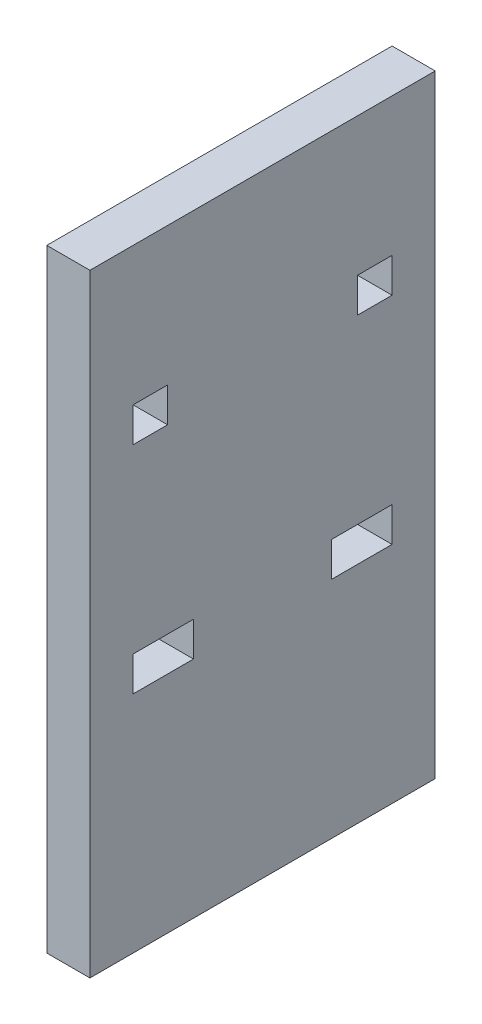
SolidWorks part; units mm, degrees
material "Mahogany"
ref_plane "Front Plane" through (0, 0, 0) normal (0, 0, 1) x (1, 0, 0)
ref_plane "Top Plane" through (0, 0, 0) normal (0, 1, 0) x (1, 0, 0)
ref_plane "Right Plane" through (0, 0, 0) normal (1, 0, 0) x (0, 0, -1)
sketch "Sketch1" plane through (0, 0, 0) normal (0, 1, 0) x (1, 0, 0)
  line L1 (-2.5, 20) -> (2.5, 20)
  line L2 (-2.5, 20) -> (-2.5, -20)
  line L3 (-2.5, -20) -> (2.5, -20)
  line L4 (2.5, 20) -> (2.5, -20)
  line L5 (-2.5, 20) -> (2.5, -20) construction
  line L6 (-2.5, -20) -> (2.5, 20) construction
  point P0 (0, 0)
  dimension "D1" = 40
  dimension "D2" = 5
extrude "Boss-Extrude1" add sketch "Sketch1" along normal blind 71
sketch "Sketch2" plane through (2.5, 0, 0) normal (1, 0, 0) x (0, 0, -1)
  line L0 (-20, 0) -> (20, 0) construction
  line L1 (-15, 30) -> (-8, 30)
  line L2 (-15, 30) -> (-15, 26)
  line L3 (-15, 26) -> (-8, 26)
  line L4 (-8, 30) -> (-8, 26)
  line L5 (-15, 30) -> (-8, 26) construction
  line L6 (-15, 26) -> (-8, 30) construction
  line L7 (-20, 71) -> (-20, 0) construction
  line L8 (0, 0) -> (0, 71) construction
  line L9 (-20, 71) -> (20, 71) construction
  line L10 (15, 26) -> (8, 30) construction
  line L11 (15, 30) -> (8, 26) construction
  line L12 (8, 30) -> (8, 26)
  line L13 (15, 26) -> (8, 26)
  line L14 (15, 30) -> (15, 26)
  line L15 (15, 30) -> (8, 30)
  line L16 (-15, 55) -> (-11, 55)
  line L17 (-15, 55) -> (-15, 51)
  line L18 (-15, 51) -> (-11, 51)
  line L19 (-11, 55) -> (-11, 51)
  line L20 (-15, 55) -> (-11, 51) construction
  line L21 (-15, 51) -> (-11, 55) construction
  line L22 (15, 51) -> (11, 55) construction
  line L23 (15, 55) -> (11, 51) construction
  line L24 (11, 55) -> (11, 51)
  line L25 (15, 51) -> (11, 51)
  line L26 (15, 55) -> (15, 51)
  line L27 (15, 55) -> (11, 55)
  point P0 (-11.5, 28)
  point P18 (11.5, 28)
  point P19 (-13, 53)
  point P29 (13, 53)
  dimension "D1" = 26
  dimension "D2" = 5
  dimension "D3" = 7
  dimension "D4" = 4
  dimension "D5" = 25
  dimension "D6" = 4
  dimension "D7" = 4
extrude "Cut-Extrude1" cut sketch "Sketch2" against normal blind 10
